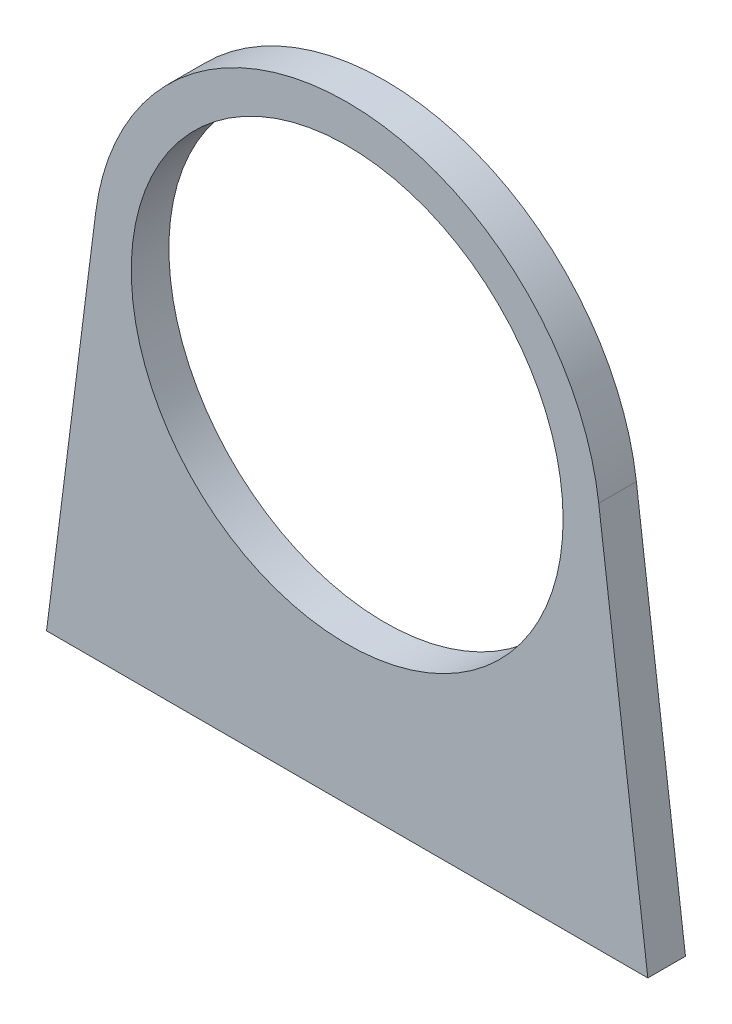
SolidWorks part; units mm, degrees
ref_plane "Front Plane" through (0, 0, 0) normal (0, 0, 1) x (1, 0, 0)
ref_plane "Top Plane" through (0, 0, 0) normal (0, 1, 0) x (1, 0, 0)
ref_plane "Right Plane" through (0, 0, 0) normal (1, 0, 0) x (0, 0, -1)
sketch "Sketch1" plane through (0, 0, 0) normal (0, 0, 1) x (1, 0, 0)
  line L0 (-16.9748, 2.1556) -> (-20.2876, -23.9309)
  line L1 (-20.2876, -23.9309) -> (20.2876, -23.9309)
  line L2 (0, 0) -> (0, -23.9309) construction
  line L3 (16.9748, 2.1556) -> (20.2876, -23.9309)
  circle A0 centre (0, 0) radius 14.5712
  arc A1 (16.9748, 2.1556) -> (-16.9748, 2.1556) centre (0, 0) ccw
  circle A2 centre (0, 0) radius 17.1112 construction
  point P8 (0, 0)
  dimension "D1" = 2.54
extrude "Boss-Extrude1" add sketch "Sketch1" along normal blind 2.54
